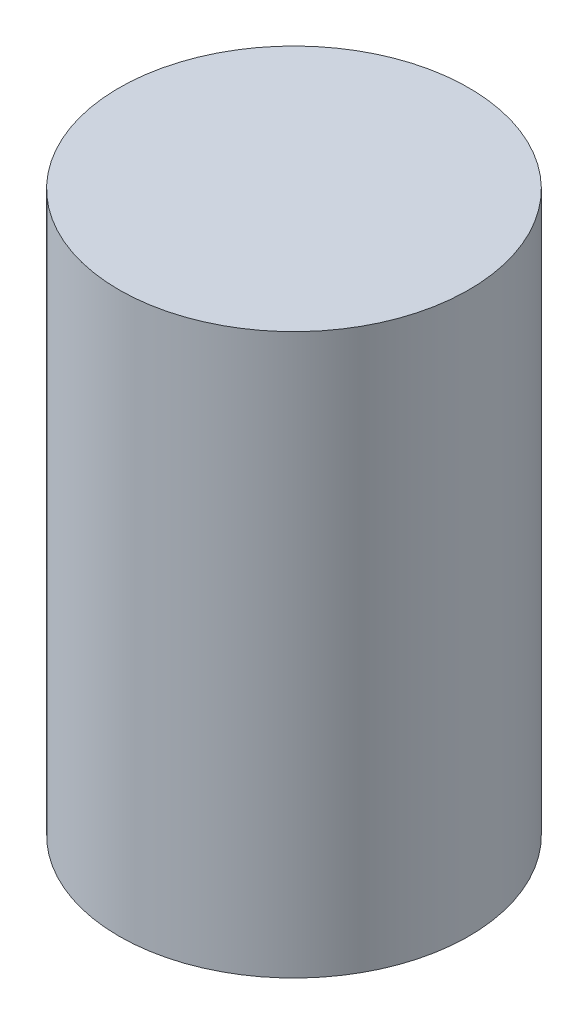
SolidWorks part; units mm, degrees
ref_plane "Front Plane" through (0, 0, 0) normal (0, 0, 1) x (1, 0, 0)
ref_plane "Top Plane" through (0, 0, 0) normal (0, 1, 0) x (1, 0, 0)
ref_plane "Right Plane" through (0, 0, 0) normal (1, 0, 0) x (0, 0, -1)
sketch "Sketch1" plane through (0, 0, 0) normal (0, 1, 0) x (1, 0, 0)
  circle A0 centre (0, 0) radius 2.5
  dimension "D1" = 5
extrude "Boss-Extrude1" add sketch "Sketch1" along normal blind 8
